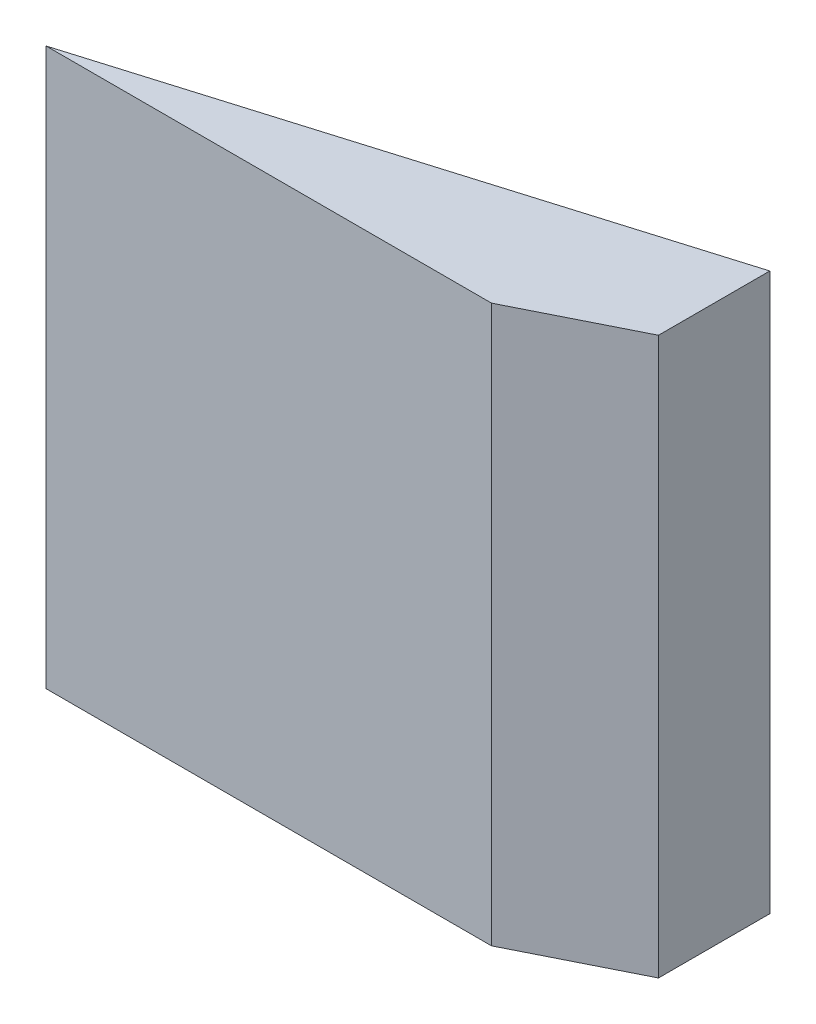
SolidWorks part; units mm, degrees
material "WhitePLA"
ref_plane "Front Plane" through (0, 0, 0) normal (0, 0, 1) x (1, 0, 0)
ref_plane "Top Plane" through (0, 0, 0) normal (0, 1, 0) x (1, 0, 0)
ref_plane "Right Plane" through (0, 0, 0) normal (1, 0, 0) x (0, 0, -1)
sketch "Sketch1" plane through (0, 0, 0) normal (0, 1, 0) x (1, 0, 0)
  line L0 (0, 0) -> (25, 7.5)
  line L1 (0, 0) -> (20, 0)
  line L2 (20, 0) -> (25, 2.5)
  line L3 (25, 7.5) -> (25, 2.5)
  dimension "D1" = 20
  dimension "D2" = 5
  dimension "D3" = 25
  dimension "D4" = 2.5
extrude "Boss-Extrude1" add sketch "Sketch1" along normal blind 25
